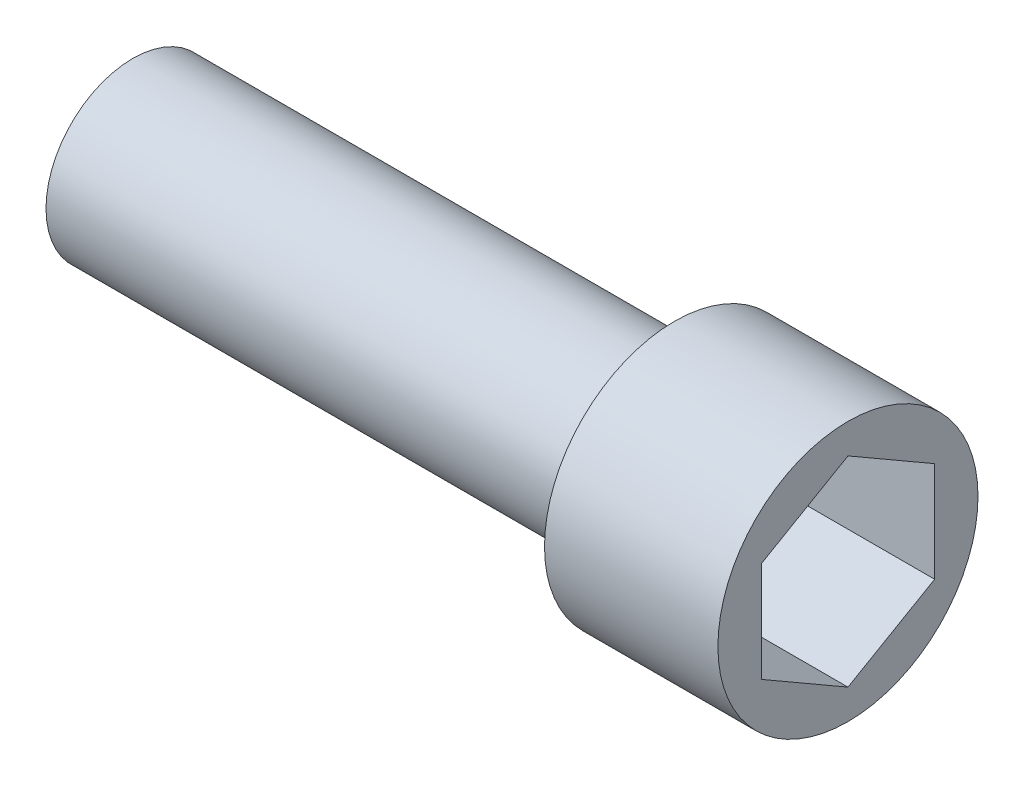
SolidWorks part; units mm, degrees
ref_plane "Front Plane" through (0, 0, 0) normal (0, 0, 1) x (1, 0, 0)
ref_plane "Top Plane" through (0, 0, 0) normal (0, 1, 0) x (1, 0, 0)
ref_plane "Right Plane" through (0, 0, 0) normal (1, 0, 0) x (0, 0, -1)
sketch "Sketch2" plane through (0, 0, 0) normal (1, 0, 0) x (0, 0, -1)
  circle A0 centre (0, 0) radius 6
  dimension "D1" = 12
extrude "Boss-Extrude1" add sketch "Sketch2" along normal blind 8
sketch "Sketch3" plane through (8, 0, 0) normal (1, 0, 0) x (0, 0, -1)
  line L1 (4, 2.3094) -> (0, 4.6188)
  line L2 (0, 4.6188) -> (-4, 2.3094)
  line L3 (-4, 2.3094) -> (-4, -2.3094)
  line L4 (-4, -2.3094) -> (0, -4.6188)
  line L5 (0, -4.6188) -> (4, -2.3094)
  line L6 (4, -2.3094) -> (4, 2.3094)
  circle A0 centre (0, 0) radius 4 construction
  dimension "D1" = 8
sketch "Sketch4" plane through (0, 0, 0) normal (-1, 0, 0) x (0, 0, 1)
  circle A0 centre (0, 0) radius 4
extrude "Boss-Extrude2" add sketch "Sketch4" along normal blind 25
extrude "Cut-Extrude1" cut sketch "Sketch3" against normal blind 7
